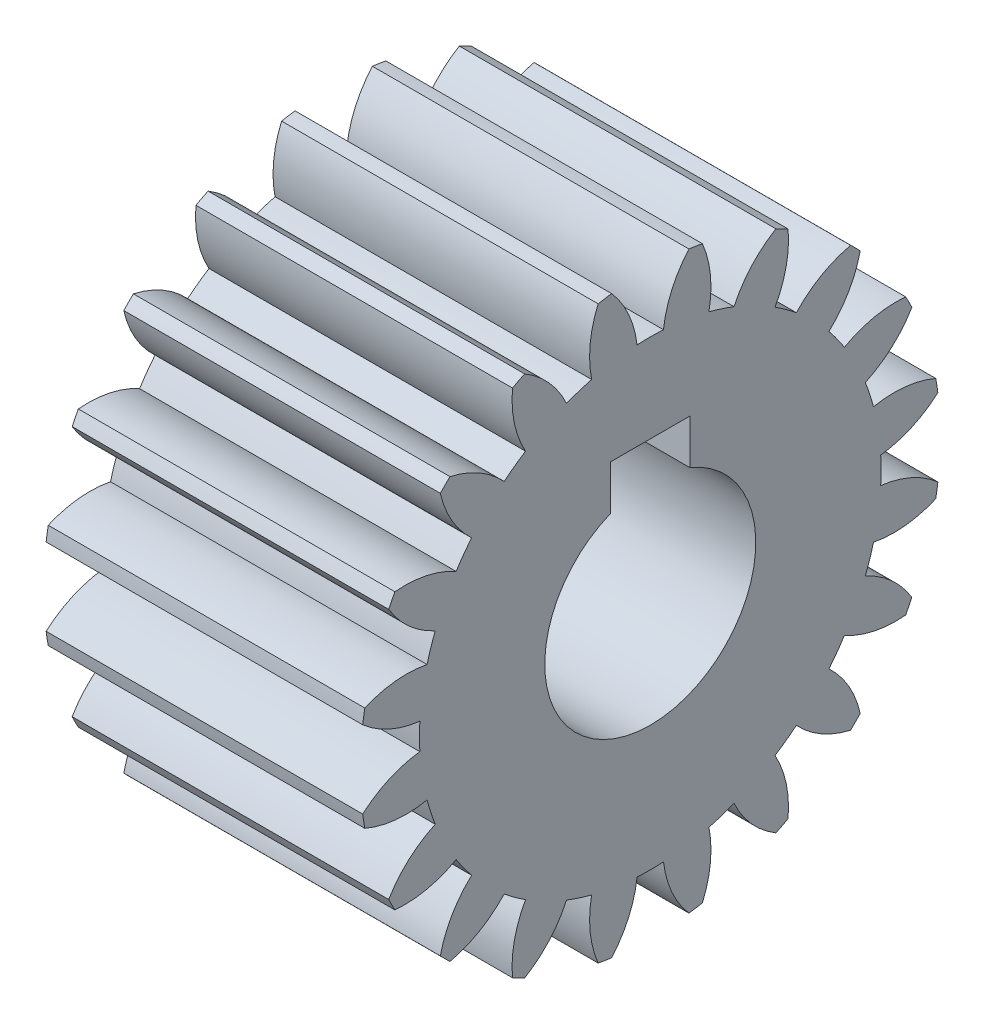
SolidWorks part; units mm, degrees
ref_plane "Plane1" through (0, 0, 0) normal (0, 0, 1) x (1, 0, 0)
ref_plane "Plane2" through (0, 0, 0) normal (0, 1, 0) x (1, 0, 0)
ref_plane "Plane3" through (0, 0, 0) normal (1, 0, 0) x (0, 0, -1)
other "Configuration Table"
sketch "HoldingSke" plane through (0, 0, 0) normal (0, 1, 0) x (1, 0, 0)
  line L0 (0, 0) -> (0.9397, -0.342)
  line L1 (-15, 0) -> (100, 0) construction
  line L2 (0, 0) -> (-2.1039, 2.3779)
  line L3 (0, 0) -> (-11.863, 4.5341)
  line L4 (0, 0) -> (8.1152, 2.9537)
  line L5 (0, 0) -> (-46.8476, -17.4728)
  line L6 (0, 0) -> (-9.9476, -6.7116)
  line L7 (-2.1039, 2.3779) -> (8.6586, 51.2059)
  line L8 (-76.2, 54.61) -> (-74.8, 54.61)
  line L9 (-71.009, 38.7566) -> (-53.1078, 45.2721)
  line L10 (-76.2, 71.12) -> (104.1128, 71.12)
  line L11 (0, 0) -> (-12, 0)
  line L12 (-76.2, 101.6) -> (-76.162, 101.6)
  line L13 (24.9733, 27.94) -> (52.9518, 28.4284)
  line L14 (24.9733, 27.94) -> (24.9743, 27.94)
  line L15 (24.9733, 27.94) -> (100.4006, 29.5858)
  line L16 (-63.627, -1) -> (-12.827, -1)
  circle A0 centre (0, 0) radius 4
  circle A1 centre (0, 0) radius 8.749
  circle A2 centre (0, 0) radius 37.5
  circle A3 centre (0, 0) radius 4
  dimension "MHD" = 17.498
  dimension "Hub_dia" = 75
  dimension "Bore" = 8
  dimension "MBD" = 8
  dimension "Num_teeth" = 20
  dimension "Pitch" = 1
  dimension "Overall_len" = 50
  dimension "Show_teeth" = 20
  dimension "Thickness" = 12
  dimension "OAL" = 50.0001
  dimension "T_dim" = 1.4
  dimension "Ap" = 20
  dimension "H" = 19.05
  dimension "Pitch_radius" = 180.3128
  dimension "Width" = 12
  dimension "Backlash" = 0.038
  dimension "Addendum_fac" = 1
  dimension "Dedendum_fac" = 1.25
  dimension "Clearance_fac" = 0.25
  dimension "Dedendum_add" = 0.001
  dimension "Module" = 1
sketch "BasProSke" plane through (0, 0, 0) normal (0, 1, 0) x (1, 0, 0)
  line L0 (-10, 0) -> (60, 0) construction
  line L1 (0, 0) -> (0, 11)
  line L2 (0, 0) -> (12, 0)
  line L3 (12, 0) -> (12, 11)
  line L4 (12, 11) -> (0, 11)
  dimension "Thickness" = 12
  dimension "Diameter" = 22
revolve "Base-Revolve" add sketch "BasProSke" angle 360 about L0
sketch "TooCutSke" plane through (0, 0, 0) normal (1, 0, 0) x (0, 0, -1)
  line L1 (0, 0) -> (0, 107) construction
  line L2 (0, 0) -> (-0.8511, 9.9637) construction
  line L3 (0, 0) -> (-3.1206, 19.7028) construction
  line L4 (-0.8511, 9.9637) -> (-1.5603, 9.8514) construction
  arc A0 (0.4999, 8.7347) -> (-0.4999, 8.7347) centre (0, 0) ccw
  arc A1 (1.4852, 10.9249) -> (-1.4852, 10.9249) centre (0, 0) ccw
  circle A2 centre (0, 0) radius 10 construction
  circle A3 centre (0, 0) radius 9.3969 construction
  arc A4 (-0.4999, 8.7347) -> (-1.4852, 10.9249) centre (-4.4722, 8.2645) ccw
  arc A5 (1.4852, 10.9249) -> (0.4999, 8.7347) centre (4.4722, 8.2645) ccw
  dimension "Root_dia" = 17.498
  dimension "Overcut_dia" = 22.0508
  dimension "Pitch_dia" = 20
  dimension "Base_dia" = 18.7939
  dimension "Flank_rad" = 4
  dimension "Half_ang" = 9
  dimension "Half_CT" = 0.7181
extrude "ToothCut" cut sketch "TooCutSke" along normal through all
fillet "Breaks" [suppressed] radius 0.02
fillet "RootFillets" [suppressed] radius 0.251
pattern_circular "TeethCuts" count 20 every 18 about axis through (-10, 0, 0) along (1, 0, 0) of "ToothCut", "RootFillets", "Breaks"
sketch "HubNeaOneSke" plane through (0, 0, 0) normal (-1, 0, 0) x (0, 0, 1)
  circle A0 centre (0, 0) radius 8.749
  dimension "Diameter" = 17.498
extrude "HubNearOne" [suppressed] add sketch "HubNeaOneSke" along normal blind 38.0001
sketch "HubNeaBotSke" plane through (0, 0, 0) normal (-1, 0, 0) x (0, 0, 1)
  circle A0 centre (0, 0) radius 8.749
  dimension "Diameter" = 17.498
extrude "HubNearBoth" [suppressed] add sketch "HubNeaBotSke" along normal blind 19
ref_plane "FarPln" through (12, 0, 0) normal (1, 0, 0) x (0, 0, -1)
sketch "HubFarSke" plane through (12, 0, 0) normal (1, 0, 0) x (0, 0, -1)
  circle A0 centre (0, 0) radius 8.749
  dimension "Diameter" = 17.498
extrude "HubFar" [suppressed] add sketch "HubFarSke" along normal blind 19
sketch "BorSke" plane through (0, 0, 0) normal (1, 0, 0) x (0, 0, -1)
  circle A0 centre (0, 0) radius 4
  dimension "Diameter" = 8
extrude "Bore" cut sketch "BorSke" along normal mid plane 100.0001
sketch "KeySke" plane through (0, 0, 0) normal (1, 0, 0) x (0, 0, -1)
  line L0 (-1.5, 0) -> (-1.5, 5.4)
  line L1 (-1.5, 5.4) -> (1.5, 5.4)
  line L2 (1.5, 5.4) -> (1.5, 0)
  line L3 (0, 0) -> (0, 34) construction
  line L4 (-1.5, 0) -> (1.5, 0)
  dimension "Offset" = 5.4
  dimension "Width" = 3
extrude "Keyway" cut sketch "KeySke" along normal mid plane 100.0001
pattern_circular "Keyway2" [suppressed] count 2 every 90 about axis through (-10, 0, 0) along (1, 0, 0)
equation "' \"Module@HoldingSke\" = 6.35"
equation "' \"Num_teeth@HoldingSke\" = 12"
equation "' \"Ap@HoldingSke\" =  20"
equation "' \"Ap@HoldingSke\" = 20"
equation "' \"Width@HoldingSke\" = 0.5 * 25.4"
equation "' \"Hub_dia@HoldingSke\"= 1 * 25.4"
equation "' \"Hub_dia@HoldingSke\" = 1 * 25.4"
equation "' \"Overall_len@HoldingSke\" = 1.0 * 25.4"
equation "' \"Bore@HoldingSke\" = 0.75 * 25.4"
equation "' \"T_dim@HoldingSke\" = 0.1 * 25.4"
equation "' \"Width@KeySke\" = 0.25 * 25.4"
equation "' \"Show_teeth@HoldingSke\" = 13"
equation "' \"Backlash@HoldingSke\" = 0.009 * 25.4"
equation "' \"Addendum_fac@HoldingSke\" = 1.0"
equation "' \"Dedendum_fac@HoldingSke\" = 1.25"
equation "' \"Dedendum_add@HoldingSke\" = 0.00005 * 25.4"
equation "' \"Clearance_fac@HoldingSke\" = 0.25"
equation "\"Pitch@HoldingSke\" = 1 / \"Module@HoldingSke\""
equation "\"Overcut_dia@TooCutSke\" = (\"Num_teeth@HoldingSke\" + 2 * \"Addendum_fac@HoldingSke\") / \"Pitch@HoldingSke\" + 0.002 * 25.4"
equation "\"Pitch_dia@TooCutSke\" = \"Num_teeth@HoldingSke\" / \"Pitch@HoldingSke\""
equation "\"Base_dia@TooCutSke\" = \"Num_teeth@HoldingSke\" / \"Pitch@HoldingSke\" * cos((\"Ap@HoldingSke\"  * 3.14159265 / 180))"
equation "\"Root_dia@TooCutSke\" = (\"Num_teeth@HoldingSke\" + 2) / \"Pitch@HoldingSke\" - 2 * (\"Addendum_fac@HoldingSke\" + \"Dedendum_fac@HoldingSke\") / \"Pitch@HoldingSke\" - \"Dedendum_add@HoldingSke\" * 2"
equation "\"Half_ang@TooCutSke\" = 180 / \"Num_teeth@HoldingSke\""
equation "\"Half_CT@TooCutSke\" = \"Num_teeth@HoldingSke\" / \"Pitch@HoldingSke\" * sin((3.14159265 / 2 / \"Num_teeth@HoldingSke\")) / 2 - 7 * \"Backlash@HoldingSke\" / 4"
equation "\"Flank_rad@TooCutSke\" = \"Num_teeth@HoldingSke\" / \"Pitch@HoldingSke\" / 5"
equation "\"Radius@RootFillets\" = \"Clearance_fac@HoldingSke\" / \"Pitch@HoldingSke\" + \"Dedendum_add@HoldingSke\""
equation "\"Break_rad@Breaks\" = 0.02 / \"Pitch@HoldingSke\""
equation "\"Thickness@HoldingSke\" = \"Width@HoldingSke\""
equation "\"OAL@HoldingSke\" = \"Thickness@HoldingSke\""
equation "\"MHD@HoldingSke\" = (\"Num_teeth@HoldingSke\" + 2) / \"Pitch@HoldingSke\" - 2 * (\"Addendum_fac@HoldingSke\" + \"Dedendum_fac@HoldingSke\")  / \"Pitch@HoldingSke\" - \"Dedendum_add@HoldingSke\" * 2"
equation "\"MBD@HoldingSke\" = (\"Num_teeth@HoldingSke\" + 2) / \"Pitch@HoldingSke\" - 2 * (\"Addendum_fac@HoldingSke\" + \"Dedendum_fac@HoldingSke\")  / \"Pitch@HoldingSke\" - \"Dedendum_add@HoldingSke\" * 2 - 0.002 * 25.4"
equation "\"MHD@HoldingSke\" = ((sgn( \"MHD@HoldingSke\" - \"Hub_dia@HoldingSke\" )-1)*( \"MHD@HoldingSke\" - \"Hub_dia@HoldingSke\" ))/-2+ \"Hub_dia@HoldingSke\""
equation "\"MBD@HoldingSke\" = ((sgn( \"MBD@HoldingSke\" - \"Bore@HoldingSke\" )-1)*( \"MBD@HoldingSke\" - \"Bore@HoldingSke\" ))/-2+ \"Bore@HoldingSke\""
equation "\"OAL@HoldingSke\" = ((sgn( \"OAL@HoldingSke\" - \"Overall_len@HoldingSke\" )+1)*( \"OAL@HoldingSke\" - \"Overall_len@HoldingSke\" ))/2 + \"Overall_len@HoldingSke\" + 0.000002 * 25.4"
equation "\"Num_teeth@TeethCuts\" = int( \"Show_teeth@HoldingSke\" ) + 1"
equation "\"Num_teeth@TeethCuts\" = ((sgn( \"Num_teeth@TeethCuts\" - \"Num_teeth@HoldingSke\" )-1)*( \"Num_teeth@TeethCuts\" - \"Num_teeth@HoldingSke\" ))/-2+ \"Num_teeth@HoldingSke\""
equation "\"Num_teeth@TeethCuts\" = ((sgn( \"Num_teeth@TeethCuts\" - 2.0)+1)*( \"Num_teeth@TeethCuts\" - 2.0))/2 +2.0"
equation "\"Angle@TeethCuts\" = 360.0 / \"Num_teeth@HoldingSke\""
equation "\"Diameter@BasProSke\" = (\"Num_teeth@HoldingSke\" + 2 * \"Addendum_fac@HoldingSke\") / \"Pitch@HoldingSke\""
equation "\"Thickness@BasProSke\"  = \"Thickness@HoldingSke\""
equation "' \"Fillet_rad@BasProSke\" =  \"Thickness@HoldingSke\" * 0.05"
equation "' \"Fillet_rad@BasProSke\" = \"Thickness@HoldingSke\" * 0.05"
equation "\"MHD@HoldingSke\" = ((sgn( \"MHD@HoldingSke\" - \"Root_dia@TooCutSke\" )-1)*( \"MHD@HoldingSke\" - \"Root_dia@TooCutSke\" ))/-2+ \"Root_dia@TooCutSke\""
equation "\"Diameter@HubNeaOneSke\" = \"MHD@HoldingSke\""
equation "\"Length@HubNearOne\" = \"OAL@HoldingSke\" - \"Thickness@BasProSke\""
equation "\"Diameter@HubNeaBotSke\" = \"MHD@HoldingSke\""
equation "\"Length@HubNearBoth\" = ( \"OAL@HoldingSke\" - \"Thickness@BasProSke\" ) / 2.0"
equation "\"Thickness@FarPln\" = \"Thickness@BasProSke\""
equation "\"Diameter@HubFarSke\" = \"MHD@HoldingSke\""
equation "\"Length@HubFar\" = ( \"OAL@HoldingSke\" - \"Thickness@BasProSke\" ) / 2.0"
equation "\"Diameter@BorSke\" = \"MBD@HoldingSke\""
equation "\"D1@Bore\" = \"OAL@HoldingSke\" * 2.0"
equation "\"D1@Keyway\" = \"OAL@HoldingSke\" * 2.0"
equation "\"Offset@KeySke\" = \"T_dim@HoldingSke\" + \"MBD@HoldingSke\" / 2.0"
